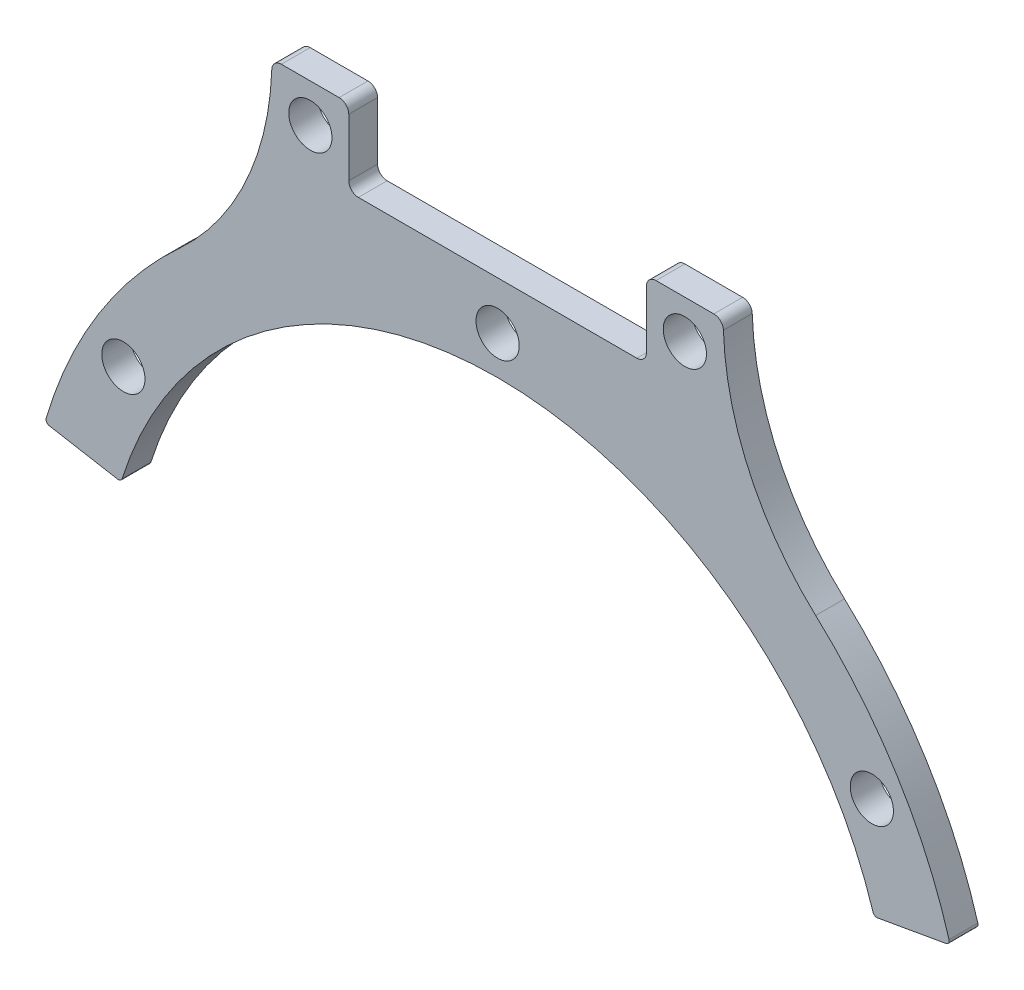
SolidWorks part; units mm, degrees
ref_plane "前视基准面" through (0, 0, 0) normal (0, 0, 1) x (1, 0, 0)
ref_plane "上视基准面" through (0, 0, 0) normal (0, 1, 0) x (1, 0, 0)
ref_plane "右视基准面" through (0, 0, 0) normal (1, 0, 0) x (0, 0, -1)
ref_plane "基准面1" through (0, 0, 0) normal (0, 0, -1) x (-1, 0, 0)
sketch "草图1" plane through (0, 0, 0) normal (0, 0, -1) x (-1, 0, 0)
  line L0 (-46.6971, -46.6889) -> (-39.5545, -47.9483)
  line L1 (39.5545, -47.9483) -> (46.6971, -46.6889)
  line L2 (22.5163, -2) -> (16.5, -2)
  line L3 (15.5, -3) -> (15.5, -9)
  line L4 (14.5, -10) -> (-14.5, -10)
  line L5 (-15.5, -9) -> (-15.5, -3)
  line L6 (-16.5, -2) -> (-22.5163, -2)
  circle A0 centre (-38.9711, -37.5) radius 2.25
  circle A1 centre (19.5, -6) radius 2.25
  circle A2 centre (38.9711, -37.5) radius 2.25
  circle A3 centre (0, -15) radius 2.25
  circle A4 centre (-19.5, -6) radius 2.25
  arc A5 (-33.1254, -23.8931) -> (-47.0114, -46.1822) centre (0, -60) ccw
  arc A6 (-47.0114, -46.1822) -> (-46.6971, -46.6889) centre (-46.6276, -46.295) ccw
  arc A7 (-39.5545, -47.9483) -> (-39.1035, -47.6747) centre (-39.485, -47.5544) ccw
  arc A8 (-39.1035, -47.6747) -> (39.1035, -47.6747) centre (0, -60) cw
  arc A9 (39.1035, -47.6747) -> (39.5545, -47.9483) centre (39.485, -47.5544) ccw
  arc A10 (46.6971, -46.6889) -> (47.0114, -46.1822) centre (46.6276, -46.295) ccw
  arc A11 (47.0114, -46.1822) -> (33.1254, -23.8931) centre (0, -60) ccw
  arc A12 (33.1254, -23.8931) -> (23.5158, -2.9674) centre (53.2108, -2) cw
  arc A13 (23.5158, -2.9674) -> (22.5163, -2) centre (22.5163, -3) ccw
  arc A14 (16.5, -2) -> (15.5, -3) centre (16.5, -3) ccw
  arc A15 (15.5, -9) -> (14.5, -10) centre (14.5, -9) cw
  arc A16 (-14.5, -10) -> (-15.5, -9) centre (-14.5, -9) cw
  arc A17 (-15.5, -3) -> (-16.5, -2) centre (-16.5, -3) ccw
  arc A18 (-22.5163, -2) -> (-23.5158, -2.9674) centre (-22.5163, -3) ccw
  arc A19 (-23.5158, -2.9674) -> (-33.1254, -23.8931) centre (-53.2108, -2) cw
extrude "凸台-拉伸1" add sketch "草图1" against normal blind 3
